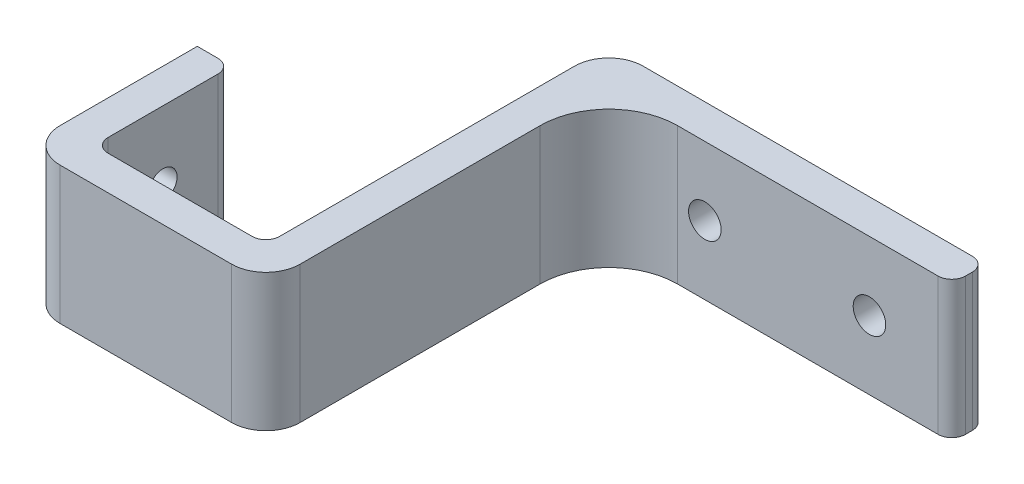
SolidWorks part; units mm, degrees
ref_plane "Front Plane" through (0, 0, 0) normal (0, 0, 1) x (1, 0, 0)
ref_plane "Top Plane" through (0, 0, 0) normal (0, 1, 0) x (1, 0, 0)
ref_plane "Right Plane" through (0, 0, 0) normal (1, 0, 0) x (0, 0, -1)
sketch "Sketch1" plane through (0, 0, 0) normal (0, 1, 0) x (1, 0, 0)
  line L0 (0, 0) -> (-5, 0)
  line L1 (-5, 0) -> (-5, -25)
  line L2 (-5, -25) -> (30, -25)
  line L3 (30, -25) -> (30, -0.5799)
  line L4 (30, -0.5799) -> (30, 25)
  line L5 (25, 30) -> (80, 30)
  line L6 (80, 30) -> (80, 25)
  line L7 (80, 25) -> (30, 25)
  line L8 (25, 30) -> (25, -20)
  line L9 (25, -20) -> (0, -20)
  line L10 (0, -20) -> (0, 0)
  point P3 (0, 0)
  point P14 (0, 0)
  point P15 (0, 0)
  dimension "D1" = 25
  dimension "D2" = 5
  dimension "D3" = 5
  dimension "D4" = 5
  dimension "D5" = 5
  dimension "D6" = 50
  dimension "D7" = 50
  dimension "D8" = 20
extrude "Boss-Extrude1" add sketch "Sketch1" along normal blind 20
sketch "Sketch2" plane through (0, 0, 0) normal (1, 0, 0) x (0, 0, -1)
  line L0 (0, 0) -> (-20, 20) construction
  line L1 (0, 20) -> (-20, 0) construction
  circle A0 centre (-10, 10) radius 2.05
  dimension "D1" = 4.1
extrude "Cut-Extrude1" cut sketch "Sketch2" against normal through all
sketch "Sketch3" plane through (0, 0, -30) normal (0, 0, -1) x (-1, 0, 0)
  line L0 (-80, 10) -> (-30, 10) construction
  line L4 (-80, 0) -> (-30, 0)
  line L5 (-80, 20) -> (-80, 0)
  line L6 (-30, 20) -> (-80, 20)
  line L7 (-30, 0) -> (-30, 20)
  line L8 (-80, 0) -> (-30, 0)
  line L9 (-80, 20) -> (-80, 0)
  line L10 (-30, 20) -> (-80, 20)
  line L11 (-30, 0) -> (-30, 20)
  circle A0 centre (-68, 10) radius 2.375
  circle A1 centre (-44, 10) radius 2.375
  dimension "D2" = 4.75
  dimension "D3" = 12
  dimension "D4" = 24
  dimension "D1" = 0
extrude "Cut-Extrude2" cut sketch "Sketch3" against normal through all contours A1 | A0
fillet "Fillet1" radius 10 1 edges at (30, 10, -25)
fillet "Fillet2" radius 5 3 edges at (-5, 10, 25) (30, 10, 25) (25, 10, -30)
fillet "Fillet3" radius 2 5 edges at (0, 10, 20) (80, 10, -30) (80, 10, -25) (0, 10, 0) (25, 10, 20)
